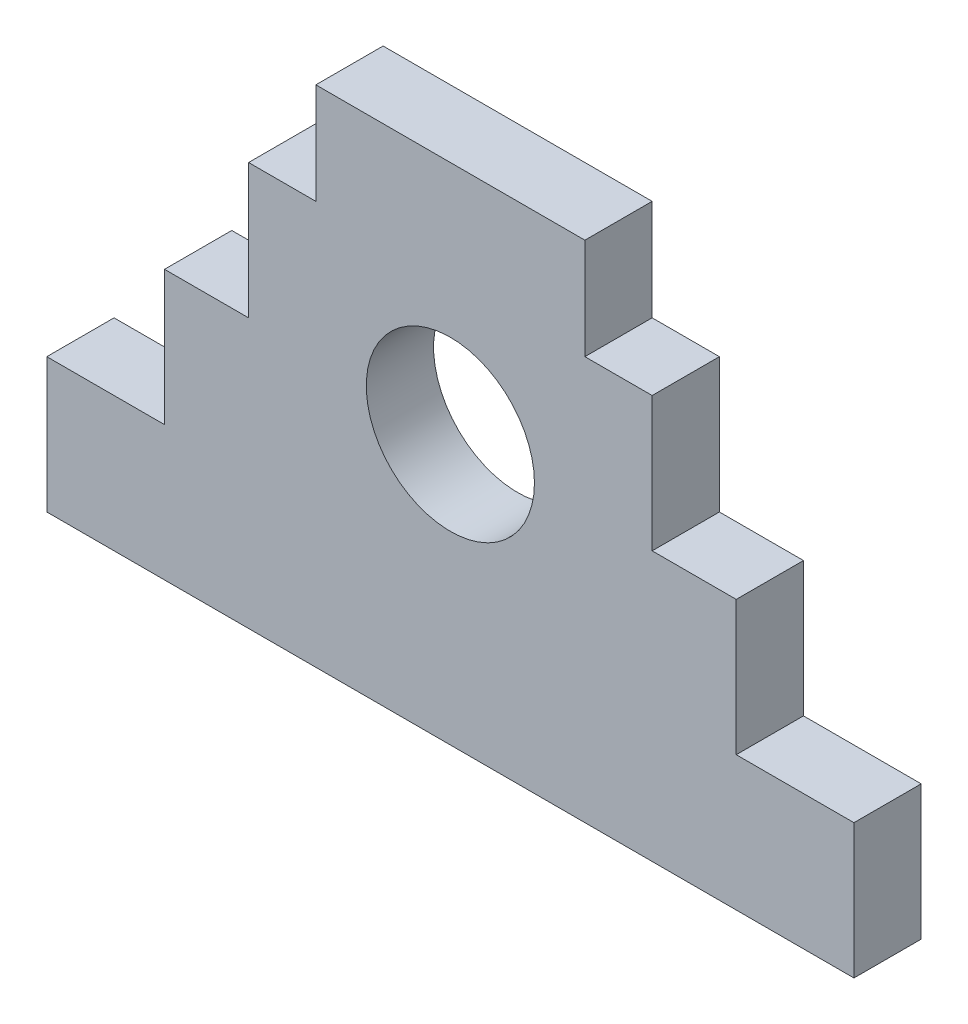
SolidWorks part; units mm, degrees
ref_plane "Front Plane" through (0, 0, 0) normal (0, 0, 1) x (1, 0, 0)
ref_plane "Top Plane" through (0, 0, 0) normal (0, 1, 0) x (1, 0, 0)
ref_plane "Right Plane" through (0, 0, 0) normal (1, 0, 0) x (0, 0, -1)
sketch "Sketch1" plane through (0, 0, 0) normal (0, 0, 1) x (1, 0, 0)
  line L0 (0, 0) -> (11.1125, 0)
  line L1 (11.1125, 0) -> (11.1125, 12.7)
  line L2 (11.1125, 12.7) -> (19.05, 12.7)
  line L3 (19.05, 12.7) -> (19.05, 25.4)
  line L4 (19.05, 25.4) -> (25.4, 25.4)
  line L5 (25.4, 25.4) -> (25.4, 34.925)
  line L6 (25.4, 34.925) -> (50.8, 34.925)
  line L7 (38.1, 34.925) -> (38.1, -9.525) construction
  line L8 (50.8, 25.4) -> (50.8, 34.925)
  line L9 (57.15, 25.4) -> (50.8, 25.4)
  line L10 (57.15, 12.7) -> (57.15, 25.4)
  line L11 (65.0875, 12.7) -> (57.15, 12.7)
  line L12 (65.0875, 0) -> (65.0875, 12.7)
  line L13 (76.2, 0) -> (65.0875, 0)
  line L14 (0, 0) -> (0, -12.7)
  line L15 (0, -12.7) -> (76.2, -12.7)
  line L16 (76.2, -12.7) -> (76.2, 0)
  circle A0 centre (38.1, 12.7) radius 7.9375
  dimension "D5" = 15.875
  dimension "D1" = 76.2
  dimension "D2" = 53.975
  dimension "D3" = 38.1
  dimension "D4" = 25.4
  dimension "D6" = 25.4
  dimension "D7" = 12.7
  dimension "D8" = 25.4
  dimension "D9" = 38.1
  dimension "D10" = 47.625
extrude "Boss-Extrude1" add sketch "Sketch1" along normal blind 6.35
